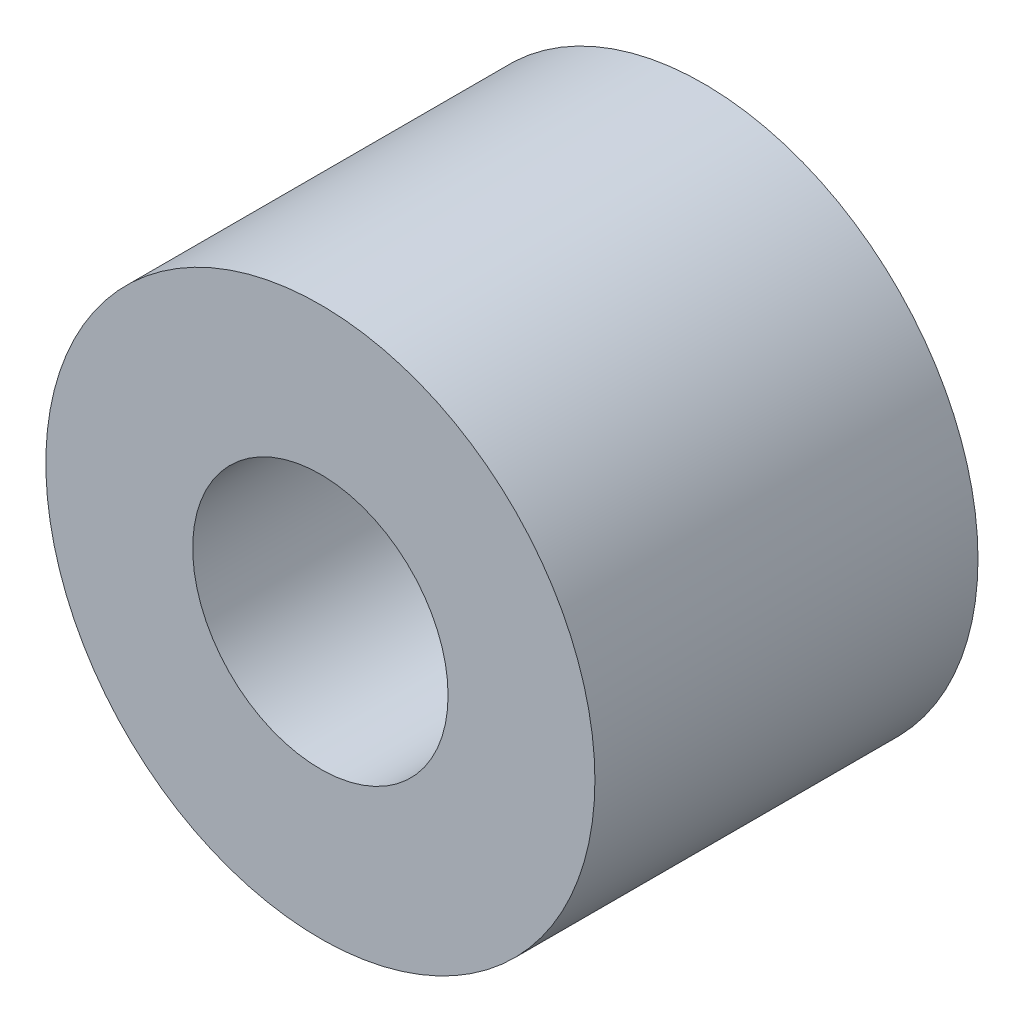
SolidWorks part; units mm, degrees
material "Copper"
ref_plane "Front Plane" through (0, 0, 0) normal (0, 0, 1) x (1, 0, 0)
ref_plane "Top Plane" through (0, 0, 0) normal (0, 1, 0) x (1, 0, 0)
ref_plane "Right Plane" through (0, 0, 0) normal (1, 0, 0) x (0, 0, -1)
sketch "Sketch1" plane through (0, 0, 0) normal (0, 0, 1) x (1, 0, 0)
  circle A0 centre (0, 0) radius 546.1
  dimension "D1" = 1092.2
extrude "Boss-Extrude1" add sketch "Sketch1" along normal blind 762
sketch "Sketch2" plane through (0, 0, 762) normal (0, 0, 1) x (1, 0, 0)
  circle A0 centre (0, 0) radius 254
  dimension "D1" = 508
extrude "Cut-Extrude1" cut sketch "Sketch2" against normal through all
